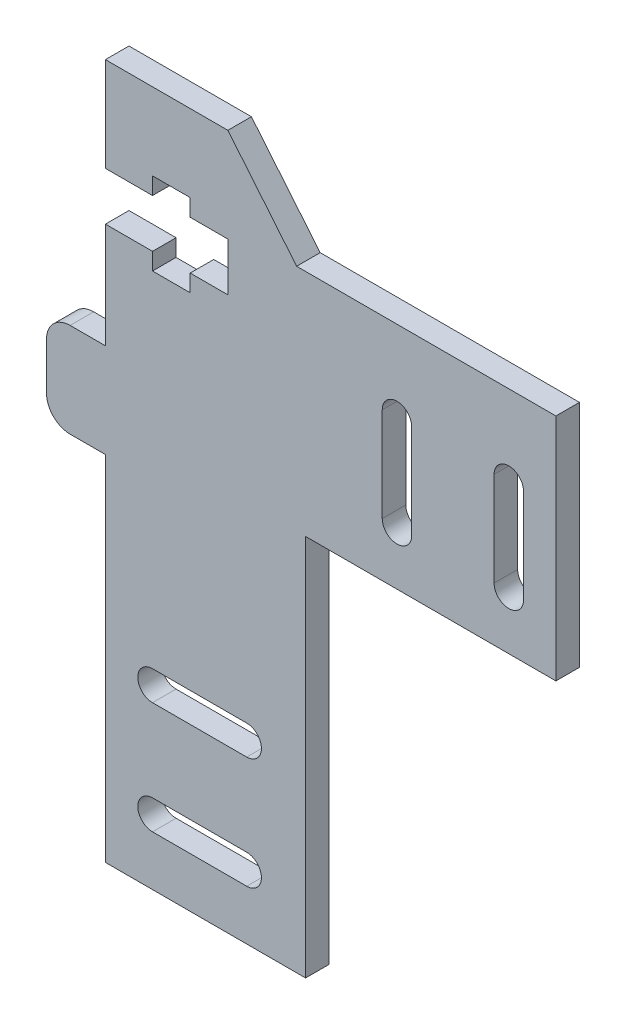
SolidWorks part; units mm, degrees
ref_plane "前视基准面" through (0, 0, 0) normal (0, 0, 1) x (1, 0, 0)
ref_plane "上视基准面" through (0, 0, 0) normal (0, 1, 0) x (1, 0, 0)
ref_plane "右视基准面" through (0, 0, 0) normal (1, 0, 0) x (0, 0, -1)
sketch "草图1" plane through (0, 0, 0) normal (0, 0, 1) x (1, 0, 0)
  line L0 (-8.3018, -11.7014) -> (-3.3018, -11.7014)
  line L1 (-8.3018, -11.7014) -> (-8.3018, -3.7014)
  line L2 (-8.3018, -3.7014) -> (-3.3018, -3.7014)
  line L3 (-3.3018, -3.7014) -> (-3.3018, 5.2486)
  line L4 (-3.3018, 5.2486) -> (0.6982, 5.2486)
  line L5 (0.6982, 5.2486) -> (0.6982, 3.7986)
  line L6 (0.6982, 3.7986) -> (3.8982, 3.7986)
  line L7 (3.8982, 3.7986) -> (3.8982, 5.2486)
  line L8 (3.8982, 5.2486) -> (7.0982, 5.2486)
  line L9 (7.0982, 5.2486) -> (7.0982, 9.3486)
  line L10 (7.0982, 9.3486) -> (3.8982, 9.3486)
  line L11 (3.8982, 9.3486) -> (3.8982, 10.7986)
  line L12 (3.8982, 10.7986) -> (0.6982, 10.7986)
  line L13 (0.6982, 10.7986) -> (0.6982, 9.3486)
  line L14 (0.6982, 9.3486) -> (-3.3018, 9.3486)
  line L15 (7.0982, 7.2986) -> (5.3982, 7.2986) construction
  line L16 (-8.3018, -7.7014) -> (-3.3018, -7.7014) construction
  line L17 (-3.3018, -11.7014) -> (-3.3018, -41.7014)
  line L18 (-3.3018, -41.7014) -> (13.6982, -41.7014)
  line L19 (13.6982, -41.7014) -> (13.6982, 17.3486) construction
  line L20 (13.6982, 17.3486) -> (-3.3018, 17.3486) construction
  line L21 (-3.3018, 17.3486) -> (-3.3018, 9.3486)
  line L22 (4.6982, -26.7014) -> (4.6982, -36.2014) construction
  line L23 (0.6982, -26.7014) -> (8.6982, -26.7014) construction
  line L24 (0.6982, -25.4514) -> (8.6982, -25.4514)
  line L25 (0.6982, -27.9514) -> (8.6982, -27.9514)
  line L26 (8.6982, -36.2014) -> (0.6982, -36.2014) construction
  line L27 (8.6982, -37.4514) -> (0.6982, -37.4514)
  line L28 (8.6982, -34.9514) -> (0.6982, -34.9514)
  line L29 (-3.3018, 17.3486) -> (7.0982, 17.3486)
  line L30 (7.0982, 17.3486) -> (13.6982, 9.3486)
  line L31 (13.6982, 9.3486) -> (34.959, 9.3486)
  line L32 (34.959, 9.3486) -> (34.959, -9.2232)
  line L33 (34.959, -9.2232) -> (13.6982, -9.2232)
  line L34 (13.6982, -9.2232) -> (13.6982, -41.7014)
  line L35 (30.959, -0.6514) -> (21.459, -0.6514) construction
  line L36 (30.959, 3.3486) -> (30.959, -4.6514) construction
  line L37 (32.209, 3.3486) -> (32.209, -4.6514)
  line L38 (29.709, 3.3486) -> (29.709, -4.6514)
  line L39 (21.459, 3.3486) -> (21.459, -4.6514) construction
  line L40 (22.709, 3.3486) -> (22.709, -4.6514)
  line L41 (20.209, 3.3486) -> (20.209, -4.6514)
  arc A0 (0.6982, -25.4514) -> (0.6982, -27.9514) centre (0.6982, -26.7014) ccw
  arc A1 (8.6982, -27.9514) -> (8.6982, -25.4514) centre (8.6982, -26.7014) ccw
  arc A2 (8.6982, -37.4514) -> (8.6982, -34.9514) centre (8.6982, -36.2014) ccw
  arc A3 (0.6982, -34.9514) -> (0.6982, -37.4514) centre (0.6982, -36.2014) ccw
  arc A4 (32.209, 3.3486) -> (29.709, 3.3486) centre (30.959, 3.3486) ccw
  arc A5 (29.709, -4.6514) -> (32.209, -4.6514) centre (30.959, -4.6514) ccw
  arc A6 (22.709, 3.3486) -> (20.209, 3.3486) centre (21.459, 3.3486) ccw
  arc A7 (20.209, -4.6514) -> (22.709, -4.6514) centre (21.459, -4.6514) ccw
  point P18 (2.2982, 3.7986)
  point P29 (4.6982, -26.7014)
  point P36 (4.6982, -36.2014)
  point P50 (30.959, -0.6514)
  point P57 (21.459, -0.6514)
  dimension "D9" = 30
  dimension "D14" = 4
  dimension "D1" = 3.2
  dimension "D2" = 4.1
  dimension "D3" = 5
  dimension "D4" = 8
  dimension "D5" = 7
  dimension "D6" = 15
  dimension "D7" = 9.5
  dimension "D8" = 8
  dimension "D10" = 34
  dimension "D11" = 17
  dimension "D12" = 8
  dimension "D13" = 9.5
  dimension "D15" = 10
extrude "凸台-拉伸1" add sketch "草图1" along normal blind 2
sketch "草图2" plane through (-3.3018, 0, 0) normal (-1, 0, 0) x (0, 0, 1)
  line L0 (1, 9.3486) -> (1, 5.2486) construction
  line L1 (2, 9.3486) -> (0, 9.3486) construction
  line L2 (2, 5.2486) -> (0, 5.2486) construction
  circle A0 centre (1, 7.2986) radius 2.05
sketch "草图4" plane through (0, 0, 2) normal (0, 0, 1) x (1, 0, 0)
  line L0 (0.6982, -36.2014) -> (8.6982, -36.2014)
  line L1 (0.6982, -26.7014) -> (8.6982, -26.7014)
  line L2 (30.959, 3.3486) -> (30.959, -4.6514)
  line L3 (21.459, 3.3486) -> (21.459, -4.6514)
fillet "圆角1" radius 2 2 edges at (-8.3018, -3.7014, 1) (-8.3018, -11.7014, 1)
sketch "草图5" plane through (0, 0, 2) normal (0, 0, 1) x (1, 0, 0)
  line L1 (34.959, 9.3486) -> (9.8562, 9.3486)
  line L2 (34.959, 9.3486) -> (34.959, 10.2686)
  line L3 (34.959, 10.2686) -> (9.8562, 10.2686)
  line L4 (9.8562, 9.3486) -> (9.8562, 10.2686)
  dimension "D1" = 0.92
extrude "凸台-拉伸2" add sketch "草图5" against normal blind 2
